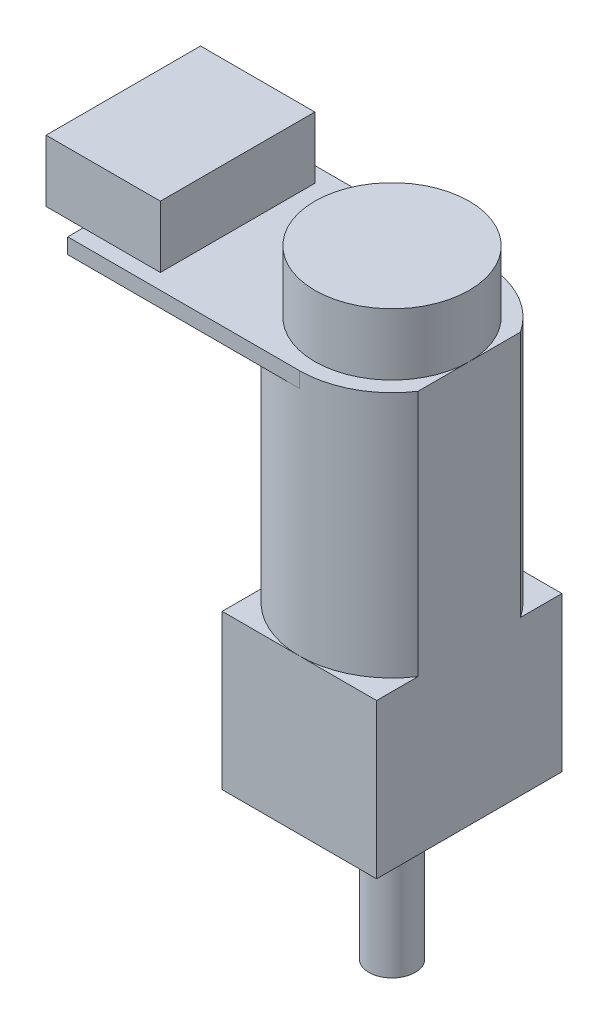
SolidWorks part; units mm, degrees
material "AISI 304"
ref_plane "前视基准面" through (0, 0, 0) normal (0, 0, 1) x (1, 0, 0)
ref_plane "上视基准面" through (0, 0, 0) normal (0, 1, 0) x (1, 0, 0)
ref_plane "右视基准面" through (0, 0, 0) normal (1, 0, 0) x (0, 0, -1)
other "Configuration Table"
sketch "草图1" plane through (0, 0, 0) normal (0, 1, 0) x (1, 0, 0)
  circle A0 centre (0, 0) radius 6
  dimension "D1" = 12
extrude "凸台-拉伸1" add sketch "草图1" along normal blind 15
sketch "草图2" plane through (0, 15, 0) normal (0, 1, 0) x (1, 0, 0)
  line L1 (-5, -8.7812) -> (5, -8.7812)
  line L2 (-5, -8.7812) -> (-5, 8.7812)
  line L3 (-5, 8.7812) -> (5, 8.7812)
  line L4 (5, -8.7812) -> (5, 8.7812)
  line L5 (-5, -8.7812) -> (5, 8.7812) construction
  line L6 (-5, 8.7812) -> (5, -8.7812) construction
  point P0 (0, 0)
  dimension "D1" = 10
extrude "切除-拉伸1" cut sketch "草图2" against normal blind 15 flip side to cut
sketch "草图3" plane through (0, 15, 0) normal (0, 1, 0) x (1, 0, 0)
  line L9 (0, -6) -> (-15, -6)
  line L10 (5, -3.3166) -> (5, 3.3166)
  line L11 (-5, 3.3166) -> (-5, -3.3166)
  line L12 (5, -3.3166) -> (5, 3.3166)
  line L15 (0, 6) -> (-15, 6)
  line L16 (-15, -6) -> (-15, 6)
  arc A6 (-5, -3.3166) -> (5, -3.3166) centre (0, 0) ccw
  arc A7 (5, 3.3166) -> (-5, 3.3166) centre (0, 0) ccw
  arc A8 (0, -6) -> (5, -3.3166) centre (0, 0) ccw
  arc A9 (5, 3.3166) -> (0, 6) centre (0, 0) ccw
  dimension "D2" = 12
  dimension "D3" = 20
  dimension "D1" = 0
extrude "凸台-拉伸2" add sketch "草图3" along normal blind 1
sketch "草图4" plane through (0, 0, 0) normal (0, -1, 0) x (1, 0, 0)
  line L1 (-5, -6) -> (5, -6)
  line L2 (-5, -6) -> (-5, 6)
  line L3 (-5, 6) -> (5, 6)
  line L4 (5, -6) -> (5, 6)
  line L5 (-5, -6) -> (5, 6) construction
  line L6 (-5, 6) -> (5, -6) construction
  point P0 (0, 0)
  dimension "D1" = 12
  dimension "D2" = 10
extrude "凸台-拉伸3" add sketch "草图4" along normal blind 10
sketch "草图5" plane through (0, -10, 0) normal (0, -1, 0) x (1, 0, 0)
  circle A0 centre (0, 0) radius 1.5
  dimension "D1" = 3
extrude "凸台-拉伸4" add sketch "草图5" along normal blind 10
sketch "草图6" plane through (0, -20, 0) normal (0, -1, 0) x (1, 0, 0)
  line L9 (-2.9967, -1) -> (3.9303, -1)
  line L10 (-2.9967, -1) -> (-2.9967, -3.0096)
  line L11 (-2.9967, -3.0096) -> (3.9303, -3.0096)
  line L12 (3.9303, -1) -> (3.9303, -3.0096)
  circle A0 centre (0, 0) radius 1.5 construction
  dimension "D1" = 1
extrude "切除-拉伸2" cut sketch "草图6" against normal up to surface (10 mm away) up to face at (0, -10, -1.5)
sketch "草图7" plane through (0, 16, 0) normal (0, 1, 0) x (1, 0, 0)
  circle A0 centre (0, 0) radius 5
  dimension "D1" = 10
extrude "凸台-拉伸5" add sketch "草图7" along normal blind 4
sketch "草图8" plane through (0, 16, 0) normal (0, 1, 0) x (1, 0, 0)
  line L1 (-17.4, 5) -> (-10, 5)
  line L2 (-17.4, 5) -> (-17.4, -5)
  line L3 (-17.4, -5) -> (-10, -5)
  line L4 (-10, 5) -> (-10, -5)
  line L5 (-10, 0) -> (-15, 0) construction
  line L6 (-15, 6) -> (-15, -6) construction
  dimension "D1" = 10
  dimension "D2" = 7.4
  dimension "D3" = 5
extrude "凸台-拉伸6" add sketch "草图8" along normal blind 4
hole_wizard "M1.4 间隙孔1" positions "草图9" profile "草图10" hole size "M1.4" standard "GB"
sketch "草图9" plane through (0, -10, 0) normal (0, -1, 0) x (-1, 0, 0)
  point P0 (-2.5, 3.75)
  point P2 (2.5, -3.75)
  dimension "D1" = 5
  dimension "D2" = 7.5
  dimension "D3" = 3.75
  dimension "D4" = 2.5
sketch "草图10" plane through (2.5, -10, -3.75) normal (1, 0, 0) x (0, 0, -1)
  line L0 (0, 0) -> (0, 10.4807)
  line L1 (0, 10.4807) -> (0.8, 10)
  line L2 (0.8, 10) -> (0.8, 0)
  line L5 (0.8, 0) -> (0, 0)
  line L10 (0, 10.4807) -> (-0.8, 10) construction
  line L11 (0, -6.35) -> (0, 107.95) construction
  dimension "孔直径" = 1.6
  dimension "孔深度" = 10
  dimension "导头角度" = 118
hole_wizard "M1.6 螺纹孔1" positions "草图11" profile "草图12" tap size "M1.6" standard "GB"
sketch "草图11" plane through (0, -10, 0) normal (0, -1, 0) x (-1, 0, 0)
  point P0 (0, 5)
  point P2 (0, -5)
  dimension "D1" = 5
  dimension "D2" = 5
sketch "草图12" plane through (0, -10, -5) normal (1, 0, 0) x (0, 0, -1)
  line L0 (0, 0) -> (0, 4.3755)
  line L1 (0, 4.3755) -> (0.625, 4)
  line L2 (0.625, 4) -> (0.625, 0)
  line L5 (0.625, 0) -> (0, 0)
  line L10 (0, 4.3755) -> (-0.625, 4) construction
  line L11 (0, -6.35) -> (0, 107.95) construction
  dimension "螺纹孔钻头直径" = 1.25
  dimension "螺纹孔钻头深度" = 4
  dimension "导头角度" = 118
cosmetic thread "孔螺蚊线1" parameters "D1"=3.2, "D2"=1.6
cosmetic thread "孔螺蚊线2" parameters "D1"=3.2, "D2"=1.6
